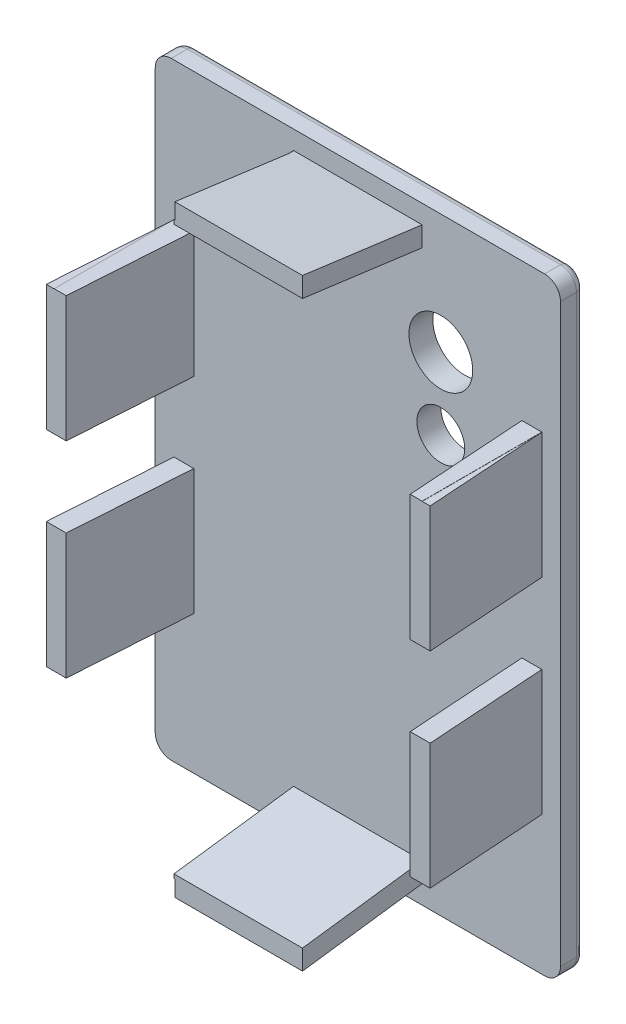
SolidWorks part; units mm, degrees
material "PLA"
ref_plane "Alzado" through (0, 0, 0) normal (0, 0, 1) x (1, 0, 0)
ref_plane "Planta" through (0, 0, 0) normal (0, 1, 0) x (1, 0, 0)
ref_plane "Vista lateral" through (0, 0, 0) normal (1, 0, 0) x (0, 0, -1)
sketch "Croquis1" plane through (0, 0, 0) normal (0, 0, 1) x (1, 0, 0)
  line L1 (25.4, 38.1) -> (-25.4, 38.1)
  line L2 (25.4, 38.1) -> (25.4, -38.1)
  line L3 (25.4, -38.1) -> (-25.4, -38.1)
  line L4 (-25.4, 38.1) -> (-25.4, -38.1)
  line L5 (25.4, 38.1) -> (-25.4, -38.1) construction
  line L6 (25.4, -38.1) -> (-25.4, 38.1) construction
  point P0 (0, 0)
  dimension "D1" = 76.2
  dimension "D2" = 50.8
extrude "Saliente-Extruir1" add sketch "Croquis1" along normal blind 18
sketch "Croquis2" plane through (0, 0, 18) normal (0, 0, 1) x (1, 0, 0)
  line L0 (25.4, 38.1) -> (-25.4, 38.1) construction
  line L1 (-23.06, 35.76) -> (23.06, 35.76)
  line L2 (-23.06, 35.76) -> (-23.06, -35.76)
  line L3 (-23.06, -35.76) -> (23.06, -35.76)
  line L4 (23.06, 35.76) -> (23.06, -35.76)
  line L5 (-25.4, -38.1) -> (25.4, -38.1) construction
  line L6 (-25.4, 38.1) -> (-25.4, -38.1) construction
  line L7 (25.4, -38.1) -> (25.4, 38.1) construction
  line L9 (-25.4, 38.1) -> (25.4, 38.1)
  line L10 (-25.4, 38.1) -> (-25.4, -38.1)
  line L11 (-25.4, -38.1) -> (25.4, -38.1)
  line L12 (25.4, 38.1) -> (25.4, -38.1)
  line L13 (-19.4, 32.1) -> (19.4, 32.1)
  line L14 (-19.4, 32.1) -> (-19.4, -32.1)
  line L15 (-19.4, -32.1) -> (19.4, -32.1)
  line L16 (19.4, 32.1) -> (19.4, -32.1)
  line M9 (-25.4, 38.1) -> (-25.4, -38.1)
  line M10 (-25.4, -38.1) -> (25.4, -38.1)
  line M11 (25.4, -38.1) -> (25.4, 38.1)
  line M12 (25.4, 38.1) -> (-25.4, 38.1)
  dimension "D1" = 2.34
  dimension "D2" = 2.34
  dimension "D3" = 2.34
  dimension "D4" = 2.34
  dimension "D5" = 6
  dimension "D6" = 6
  dimension "D7" = 6
  dimension "D8" = 6
extrude "Cortar-Extruir1" cut sketch "Croquis2" against normal blind 15 contours L1 L4 L3 L2 M12 M9 M10 M11 | L16 L13 L14 L15
sketch "Croquis3" plane through (0, 0, 18) normal (0, 0, 1) x (1, 0, 0)
  line L0 (-23.06, 35.76) -> (-23.06, -35.76) construction
  line L1 (-23.06, 22.1) -> (-19.4, 22.1)
  line L2 (-23.06, 22.1) -> (-23.06, -22.1)
  line L3 (-23.06, -22.1) -> (-19.4, -22.1)
  line L4 (-19.4, 22.1) -> (-19.4, -22.1)
  line L5 (-19.4, 32.1) -> (-19.4, -32.1) construction
  line L6 (-19.4, -32.1) -> (19.4, -32.1) construction
  line L7 (-9.4, -32.1) -> (9.3837, -32.1)
  line L8 (-9.4, -32.1) -> (-9.4, -35.76)
  line L9 (-9.4, -35.76) -> (9.3837, -35.76)
  line L10 (9.3837, -32.1) -> (9.3837, -35.76)
  line L11 (-23.06, -35.76) -> (23.06, -35.76) construction
  line L12 (19.4, 32.1) -> (19.4, -32.1) construction
  line L13 (19.4, -22.1) -> (23.06, -22.1)
  line L14 (19.4, -22.1) -> (19.4, 22.1)
  line L15 (19.4, 22.1) -> (23.06, 22.1)
  line L16 (23.06, -22.1) -> (23.06, 22.1)
  line L17 (23.06, 35.76) -> (23.06, -35.76) construction
  line L18 (-23.06, 35.76) -> (23.06, 35.76) construction
  line L19 (-9.4, 35.76) -> (9.4, 35.76)
  line L20 (-9.4, 35.76) -> (-9.4, 32.1)
  line L21 (-9.4, 32.1) -> (9.4, 32.1)
  line L22 (9.4, 35.76) -> (9.4, 32.1)
  line L23 (-19.4, 32.1) -> (19.4, 32.1) construction
  line L24 (-19.4, 32.1) -> (-19.4, -32.1) construction
  line L25 (19.4, 32.1) -> (19.4, -32.1) construction
  dimension "D1" = 10
  dimension "D2" = 10
  dimension "D3" = 10
  dimension "D4" = 10
  dimension "D5" = 10
  dimension "D6" = 10
  dimension "D7" = 10
extrude "Cortar-Extruir2" [suppressed] cut sketch "Croquis3" against normal blind 7
fillet "Redondeo1" [suppressed] radius 2
fillet "Redondeo2" [suppressed] radius 1
sketch "Croquis5" [suppressed] plane through (0, -38.1, 0) normal (0, -1, 0) x (1, 0, 0)
  line L0 (-23.4, 3) -> (23.4, 3) construction
  line L1 (-3, 3) -> (3, 3)
  line L2 (-3, 3) -> (-3, 1.5)
  line L3 (-3, 1.5) -> (3, 1.5)
  line L4 (3, 3) -> (3, 1.5)
  line L5 (0, 1) -> (0, 3) construction
  line L6 (-23.4, 1) -> (23.4, 1) construction
  dimension "D1" = 3
  dimension "D2" = 3
  dimension "D3" = 1.5
extrude "Cortar-Extruir4" [suppressed] cut sketch "Croquis5" against normal blind 6
sketch "Croquis6" plane through (0, 0, 18) normal (0, 0, 1) x (1, 0, 0)
  line L0 (-23.06, 35.76) -> (-8.06, 35.76)
  line L1 (-23.06, 35.76) -> (23.06, 35.76) construction
  line L2 (-8.06, 35.76) -> (-8.06, 32.1)
  line L3 (-19.4, 32.1) -> (19.4, 32.1) construction
  line L4 (-8.06, 32.1) -> (-19.4, 32.1)
  line L5 (-19.4, 32.1) -> (-19.4, 20.76)
  line L6 (-19.4, 32.1) -> (-19.4, -32.1) construction
  line L7 (-19.4, 20.76) -> (-23.06, 20.76)
  line L8 (-23.06, 35.76) -> (-23.06, -35.76) construction
  line L9 (-23.06, 20.76) -> (-23.06, 35.76)
  line L10 (23.06, 35.76) -> (8.06, 35.76)
  line L11 (-23.06, 35.76) -> (23.06, 35.76) construction
  line L12 (8.06, 35.76) -> (8.06, 32.1)
  line L13 (8.06, 32.1) -> (19.4, 32.1)
  line L14 (19.4, 32.1) -> (19.4, -32.1) construction
  line L15 (19.4, 32.1) -> (19.4, -32.1) construction
  line L16 (19.4, 32.1) -> (19.4, 20.76)
  line L17 (19.4, 20.76) -> (23.06, 20.76)
  line L18 (23.06, 35.76) -> (23.06, -35.76) construction
  line L19 (23.06, 20.76) -> (23.06, 35.76)
  line L20 (-23.06, -35.76) -> (-23.06, -20.76)
  line L21 (-23.06, 35.76) -> (-23.06, -35.76) construction
  line L22 (-23.06, -20.76) -> (-19.4, -20.76)
  line L23 (-19.4, 32.1) -> (-19.4, -32.1) construction
  line L24 (-19.4, -20.76) -> (-19.4, -32.1)
  line L25 (-19.4, -32.1) -> (-8.06, -32.1)
  line L26 (-19.4, -32.1) -> (19.4, -32.1) construction
  line L27 (-8.06, -32.1) -> (-8.06, -35.76)
  line L28 (-23.06, -35.76) -> (23.06, -35.76) construction
  line L29 (-8.06, -35.76) -> (-23.06, -35.76)
  line L30 (23.06, -35.76) -> (8.06, -35.76)
  line L31 (-23.06, -35.76) -> (23.06, -35.76) construction
  line L32 (8.06, -35.76) -> (8.06, -32.1)
  line L33 (-19.4, -32.1) -> (19.4, -32.1) construction
  line L34 (8.06, -32.1) -> (19.4, -32.1)
  line L35 (19.4, -32.1) -> (19.4, -20.76)
  line L36 (19.4, -20.76) -> (23.06, -20.76)
  line L37 (23.06, 35.76) -> (23.06, -35.76) construction
  line L38 (23.06, -20.76) -> (23.06, -35.76)
  dimension "D1" = 15
  dimension "D2" = 15
  dimension "D3" = 15
  dimension "D4" = 15
  dimension "D5" = 15
  dimension "D6" = 15
  dimension "D7" = 15
  dimension "D8" = 15
extrude "Cortar-Extruir8" cut sketch "Croquis6" against normal blind 15
sketch "Croquis10" plane through (0, -20.76, 0) normal (0, -1, 0) x (-1, 0, 0)
  line L0 (23.06, -18) -> (24.06, -18)
  line L1 (24.06, -18) -> (23.06, -3)
  line L2 (23.06, -3) -> (23.06, -18)
  line L3 (-23.06, -18) -> (-24.06, -18)
  line L4 (-24.06, -18) -> (-23.06, -3)
  line L5 (-23.06, -3) -> (-23.06, -18)
  dimension "D1" = 1
  dimension "D2" = 1
extrude "Saliente-Extruir3" add sketch "Croquis10" against normal blind 41.5
sketch "Croquis11" plane through (0, -20.76, 0) normal (0, -1, 0) x (1, 0, 0)
  line L0 (-19.4, 18) -> (-21.56, 18)
  line L1 (-19.4, 18) -> (-24.06, 18) construction
  line L2 (-21.56, 18) -> (-20.56, 3)
  line L3 (-19.4, 3) -> (-23.06, 3) construction
  line L4 (-20.56, 3) -> (-19.4, 3)
  line L5 (-19.4, 18) -> (-19.4, 3)
  dimension "D1" = 2.5
  dimension "D2" = 1.16
extrude "Cortar-Extruir9" cut sketch "Croquis11" against normal blind 51.5
sketch "Croquis12" plane through (0, -20.76, 0) normal (0, -1, 0) x (1, 0, 0)
  line L0 (19.4, 18) -> (19.4, 3)
  line L1 (19.4, 3) -> (20.56, 3)
  line L2 (23.06, 3) -> (19.4, 3) construction
  line L3 (20.56, 3) -> (21.56, 18)
  line L4 (24.06, 18) -> (19.4, 18) construction
  line L5 (21.56, 18) -> (19.4, 18)
  dimension "D1" = 2.5
  dimension "D2" = 1.16
extrude "Cortar-Extruir10" cut sketch "Croquis12" against normal blind 51.5
sketch "Croquis13" plane through (8.06, 0, 0) normal (1, 0, 0) x (0, 0, -1)
  line L0 (-18, -35.76) -> (-18, -37.76)
  line L1 (-18, -37.76) -> (-3, -35.76)
  line L2 (-3, -35.76) -> (-18, -35.76)
  line L3 (-18, 35.76) -> (-18, 37.76)
  line L4 (-18, 37.76) -> (-3, 35.76)
  line L5 (-3, 35.76) -> (-18, 35.76)
  dimension "D1" = 2
  dimension "D2" = 2
extrude "Saliente-Extruir4" add sketch "Croquis13" against normal blind 16
sketch "Croquis14" plane through (8.06, 0, 0) normal (1, 0, 0) x (0, 0, -1)
  line L0 (-3, -32.1) -> (-18, -32.1)
  line L1 (-18, -32.1) -> (-18, -35.26)
  line L2 (-18, -32.1) -> (-18, -37.76) construction
  line L3 (-18, -35.26) -> (-3, -33.26)
  line L4 (-3, -32.1) -> (-3, -35.76) construction
  line L5 (-3, -33.26) -> (-3, -32.1)
  line L6 (-18, 32.1) -> (-18, 35.26)
  line L7 (-18, 37.76) -> (-18, 32.1) construction
  line L8 (-18, 35.26) -> (-3, 33.26)
  line L9 (-3, 35.76) -> (-3, 32.1) construction
  line L10 (-3, 33.26) -> (-3, 32.1)
  line L11 (-3, 32.1) -> (-18, 32.1)
  dimension "D1" = 2.5
  dimension "D2" = 1.16
  dimension "D3" = 2.5
  dimension "D4" = 1.16
extrude "Cortar-Extruir11" cut sketch "Croquis14" against normal blind 16.5
fillet "Redondeo3" radius 2 4 edges at (25.4, 38.1, 1.5) (-25.4, 38.1, 1.5) (-25.4, -38.1, 1.5) (25.4, -38.1, 1.5)
fillet "Redondeo4" radius 1 8 edges at (-24.8142, 37.5142, 0) (-25.4, 0, 0) (-24.8142, -37.5142, 0) (0, -38.1, 0) (24.8142, -37.5142, 0) (25.4, 0, 0) (24.8142, 37.5142, 0) (0, 38.1, 0)
sketch "Croquis15" plane through (0, 0, 18) normal (0, 0, 1) x (1, 0, 0)
  line L0 (-24.06, -0.01) -> (24.06, -0.01) construction
  line L1 (-24.06, 20.74) -> (-24.06, -20.76) construction
  line L2 (24.06, 20.74) -> (24.06, -20.76) construction
  line L4 (-24.06, 4.99) -> (24.06, 4.99)
  line L5 (-24.06, 4.99) -> (-24.06, -5.01)
  line L6 (-24.06, -5.01) -> (24.06, -5.01)
  line L7 (24.06, 4.99) -> (24.06, -5.01)
  dimension "D1" = 5
  dimension "D2" = 5
extrude "Cortar-Extruir12" cut sketch "Croquis15" against normal blind 15
sketch "Croquis16" plane through (0, -38.1, 0) normal (0, -1, 0) x (1, 0, 0)
  line L0 (-23.4, 3) -> (23.4, 3) construction
  line L1 (-4, 3) -> (4, 3)
  line L2 (-4, 3) -> (-4, 1.5)
  line L3 (-4, 1.5) -> (4, 1.5)
  line L4 (4, 3) -> (4, 1.5)
  dimension "D1" = 1.5
  dimension "D2" = 8
  dimension "D3" = 4
extrude "Cortar-Extruir13" cut sketch "Croquis16" against normal blind 2
sketch "Croquis17" plane through (0, 0, 3) normal (0, 0, 1) x (1, 0, 0)
  line L0 (23.4, 38.1) -> (-23.4, 38.1) construction
  line L2 (25.4, -36.1) -> (25.4, 36.1) construction
  circle A0 centre (10.4, 23.1) radius 4
  circle A2 centre (10.4, 14.1) radius 3
  dimension "D3" = 8
  dimension "D4" = 9
  dimension "D5" = 6
  dimension "D1" = 15
  dimension "D2" = 15
  dimension "D6" = 15
extrude "Cortar-Extruir14" cut sketch "Croquis17" against normal blind 10
